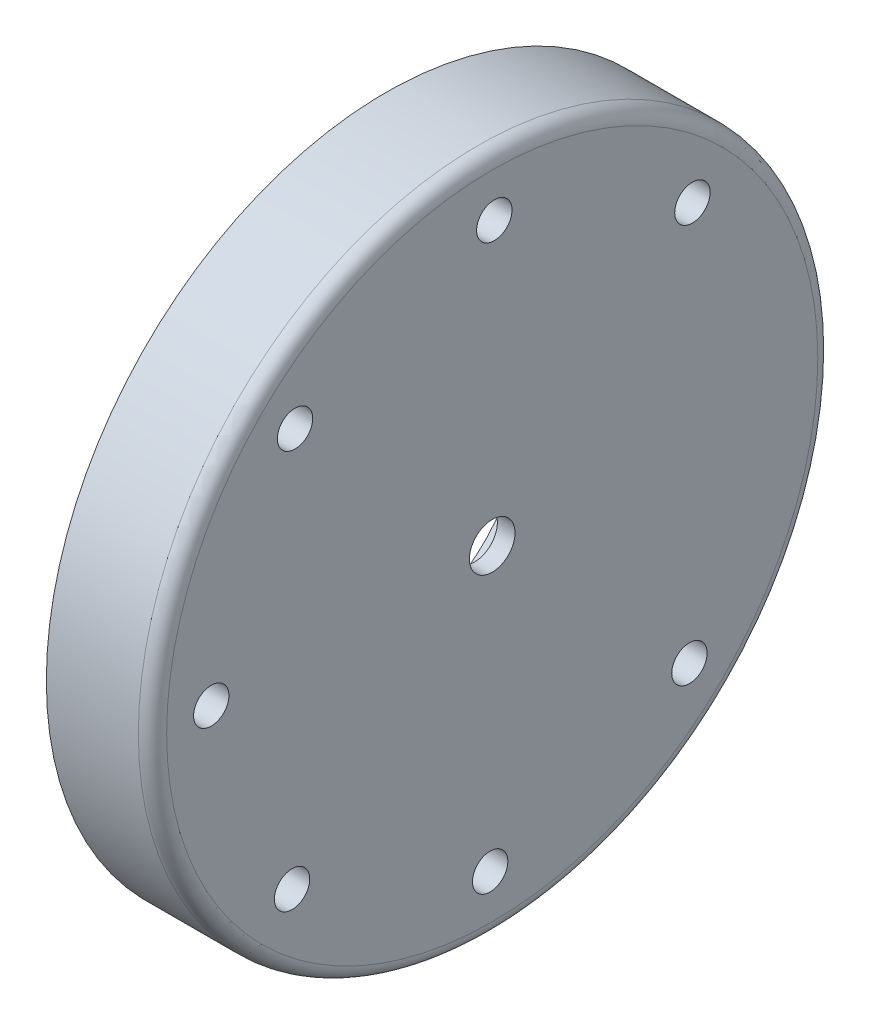
SolidWorks part; units mm, degrees
ref_plane "Front Plane" through (0, 0, 0) normal (0, 0, 1) x (1, 0, 0)
ref_plane "Top Plane" through (0, 0, 0) normal (0, 1, 0) x (1, 0, 0)
ref_plane "Right Plane" through (0, 0, 0) normal (1, 0, 0) x (0, 0, -1)
sketch "Sketch1" plane through (0, 0, 0) normal (1, 0, 0) x (0, 0, -1)
  circle A0 centre (0, 0) radius 60.96
extrude "Boss-Extrude1" add sketch "Sketch1" along normal blind 19.05
fillet "Fillet1" radius 2.54 1 edges at (19.05, 0, -60.96)
sketch "Sketch2" plane through (19.05, 0, 0) normal (1, 0, 0) x (0, 0, -1)
  circle A0 centre (0, 0) radius 4
extrude "Cut-Extrude1" cut sketch "Sketch2" against normal blind 6.35
sketch "Sketch3" plane through (19.05, 0, 0) normal (1, 0, 0) x (0, 0, -1)
  circle A0 centre (22.5439, 0) radius 3.175
extrude "Cut-Extrude2" [suppressed] cut sketch "Sketch3" against normal blind 19.05
pattern_circular "CirPattern1" [suppressed] count 8 over 360
sketch "Sketch4" plane through (19.05, 0, 0) normal (1, 0, 0) x (0, 0, -1)
  circle A0 centre (0, 0) radius 25.019
extrude "Cut-Extrude3" cut sketch "Sketch4" against normal through all
sketch "Sketch5" plane through (0, 0, 0) normal (-1, 0, 0) x (0, 0, 1)
  circle A0 centre (-35.9173, 35.3839) radius 3.175
extrude "Cut-Extrude4" cut sketch "Sketch5" against normal through all contours A0
pattern_circular "CirPattern2" count 8 over 360 about axis through (0, 0, 0) along (1, 0, 0) skipping 7 of "Cut-Extrude4"
sketch "Sketch6" plane through (19.05, 0, 0) normal (1, 0, 0) x (0, 0, -1)
  circle A0 centre (0, 0) radius 25.019
  circle A1 centre (0, 0) radius 4.0957
extrude "Boss-Extrude2" add sketch "Sketch6" against normal blind 3.175
